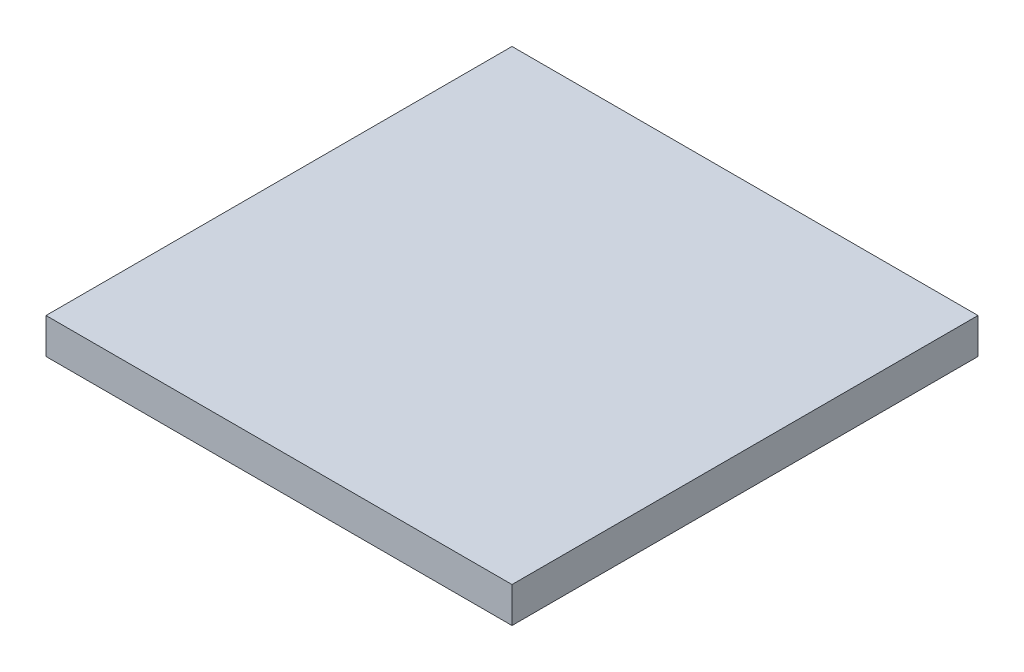
SolidWorks part; units mm, degrees
ref_plane "Front Plane" through (0, 0, 0) normal (0, 0, 1) x (1, 0, 0)
ref_plane "Top Plane" through (0, 0, 0) normal (0, 1, 0) x (1, 0, 0)
ref_plane "Right Plane" through (0, 0, 0) normal (1, 0, 0) x (0, 0, -1)
sketch "Sketch1" plane through (0, 0, 0) normal (0, 1, 0) x (1, 0, 0)
  line L1 (0, 0) -> (40, 0)
  line L2 (0, 0) -> (0, 40)
  line L3 (0, 40) -> (40, 40)
  line L4 (40, 0) -> (40, 40)
  dimension "D1" = 40
  dimension "D2" = 40
extrude "Boss-Extrude1" add sketch "Sketch1" along normal blind 3.05
